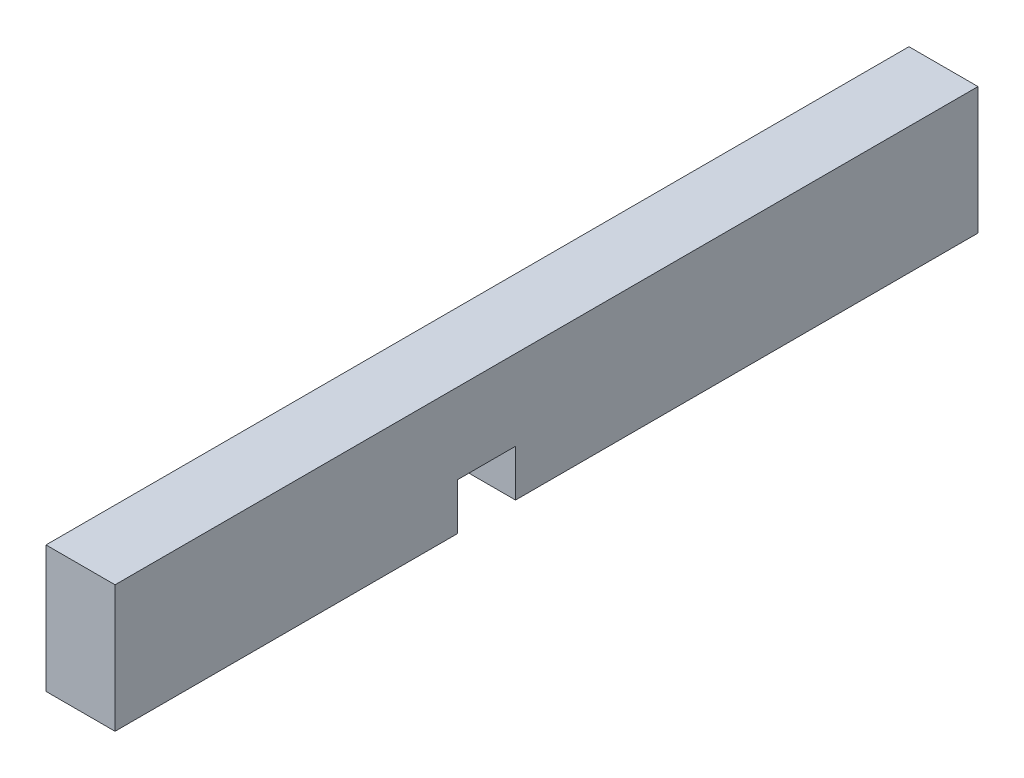
SolidWorks part; units mm, degrees
ref_plane "Front Plane" through (0, 0, 0) normal (0, 0, 1) x (1, 0, 0)
ref_plane "Top Plane" through (0, 0, 0) normal (0, 1, 0) x (1, 0, 0)
ref_plane "Right Plane" through (0, 0, 0) normal (1, 0, 0) x (0, 0, -1)
sketch "Sketch1" plane through (0, 0, 0) normal (1, 0, 0) x (0, 0, -1)
  line L1 (-29.3624, -4.318) -> (29.3624, -4.318)
  line L2 (-29.3624, -4.318) -> (-29.3624, 4.318)
  line L3 (-29.3624, 4.318) -> (29.3624, 4.318)
  line L4 (29.3624, -4.318) -> (29.3624, 4.318)
  line L5 (-29.3624, -4.318) -> (29.3624, 4.318) construction
  line L6 (-29.3624, 4.318) -> (29.3624, -4.318) construction
  point P0 (0, 0)
  dimension "D1" = 58.7248
  dimension "D2" = 8.636
extrude "Boss-Extrude1" add sketch "Sketch1" along normal mid plane 4.699
sketch "Sketch2" plane through (2.3495, 0, 0) normal (1, 0, 0) x (0, 0, -1)
  line L0 (-29.3624, -4.318) -> (29.3624, -4.318) construction
  line L1 (-6.071, -4.318) -> (-2.1086, -4.318)
  line L2 (-6.071, -4.318) -> (-6.071, -1.143)
  line L3 (-6.071, -1.143) -> (-2.1086, -1.143)
  line L4 (-2.1086, -4.318) -> (-2.1086, -1.143)
  dimension "D1" = 3.9624
  dimension "D2" = 3.175
extrude "Cut-Extrude1" cut sketch "Sketch2" against normal up to surface (4.699 mm away) up to face at (-2.3495, 0, 0)
